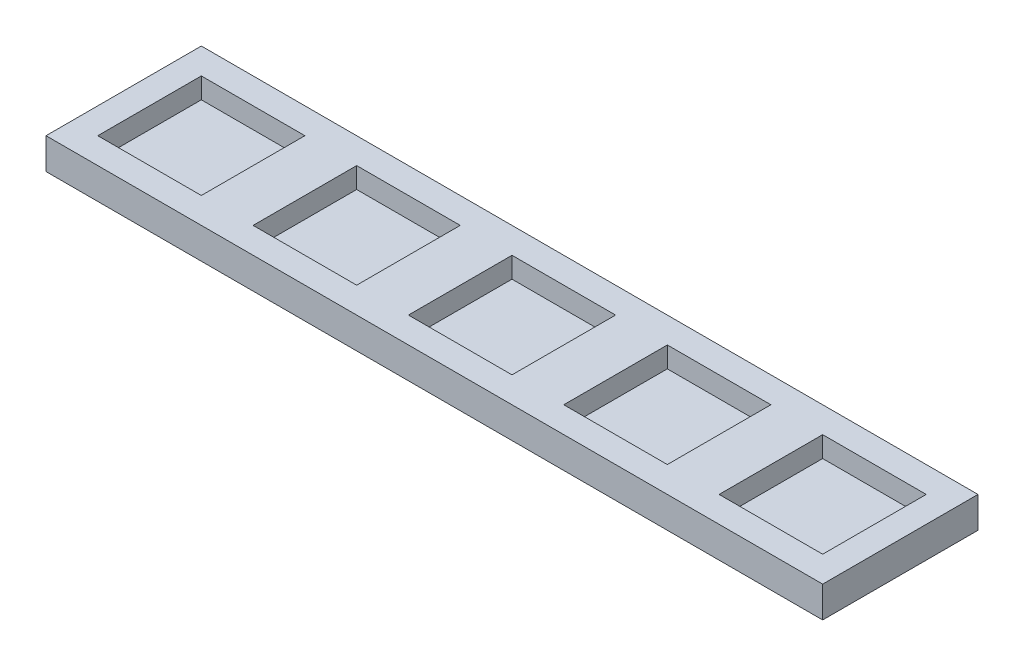
SolidWorks part; units mm, degrees
ref_plane "前视基准面" through (0, 0, 0) normal (0, 0, 1) x (1, 0, 0)
ref_plane "上视基准面" through (0, 0, 0) normal (0, 1, 0) x (1, 0, 0)
ref_plane "右视基准面" through (0, 0, 0) normal (1, 0, 0) x (0, 0, -1)
sketch "草图1" plane through (0, 0, 0) normal (0, 1, 0) x (1, 0, 0)
  line L0 (375, 0) -> (-375, 0)
  line L1 (-375, 0) -> (-375, -150)
  line L2 (-375, -150) -> (375, -150)
  line L3 (375, -150) -> (375, 0)
  point P4 (0, 0)
  dimension "D1" = 750
  dimension "D2" = 150
extrude "凸台-拉伸1" add sketch "草图1" along normal blind 30
sketch "草图2" plane through (0, 30, 0) normal (0, 1, 0) x (1, 0, 0)
  line L0 (-225, 0) -> (-225, -150) construction
  line L1 (-75, 0) -> (-75, -150) construction
  line L2 (75, 0) -> (75, -150) construction
  line L3 (225, 0) -> (225, -150) construction
  line L4 (-375, -150) -> (375, -150)
  line L5 (375, -150) -> (375, 0)
  line L6 (375, 0) -> (-375, 0)
  line L7 (-375, 0) -> (-375, -150)
  line L8 (-375, -150) -> (375, -150) construction
  line L9 (375, -150) -> (375, 0) construction
  line L10 (375, 0) -> (-375, 0) construction
  line L11 (-375, 0) -> (-375, -150) construction
  line L12 (-375, 0) -> (-225, -150) construction
  line L13 (-375, -150) -> (-225, 0) construction
  line L14 (-200, -25) -> (-100, -25)
  line L15 (-350, -25) -> (-250, -25)
  line L16 (-350, -25) -> (-350, -125)
  line L17 (-350, -125) -> (-250, -125)
  line L18 (-250, -25) -> (-250, -125)
  line L19 (-300, -125) -> (-300, -25) construction
  line L20 (-350, -75) -> (-250, -75) construction
  line L21 (-200, -25) -> (-200, -125)
  line L22 (-200, -125) -> (-100, -125)
  line L23 (-100, -25) -> (-100, -125)
  line L24 (-50, -25) -> (50, -25)
  line L25 (-50, -25) -> (-50, -125)
  line L26 (-50, -125) -> (50, -125)
  line L27 (50, -25) -> (50, -125)
  line L28 (100, -25) -> (200, -25)
  line L29 (100, -25) -> (100, -125)
  line L30 (100, -125) -> (200, -125)
  line L31 (200, -25) -> (200, -125)
  line L32 (250, -25) -> (350, -25)
  line L33 (250, -25) -> (250, -125)
  line L34 (250, -125) -> (350, -125)
  line L35 (350, -25) -> (350, -125)
  point P2 (-300, -75)
  dimension "D3" = 150
  dimension "D4" = 100
  dimension "D5" = 5
  dimension "D6" = 150
  dimension "D1" = 0
  dimension "D2" = 5
extrude "切除-拉伸1" cut sketch "草图2" against normal blind 20
sketch "草图3" plane through (0, 0, 0) normal (0, -1, 0) x (1, 0, 0)
  line L0 (-375, 150) -> (375, 150) construction
  line L1 (-375, 150) -> (375, 150) construction
  line L2 (0, 150) -> (0, -200) construction
  dimension "D1" = 350
